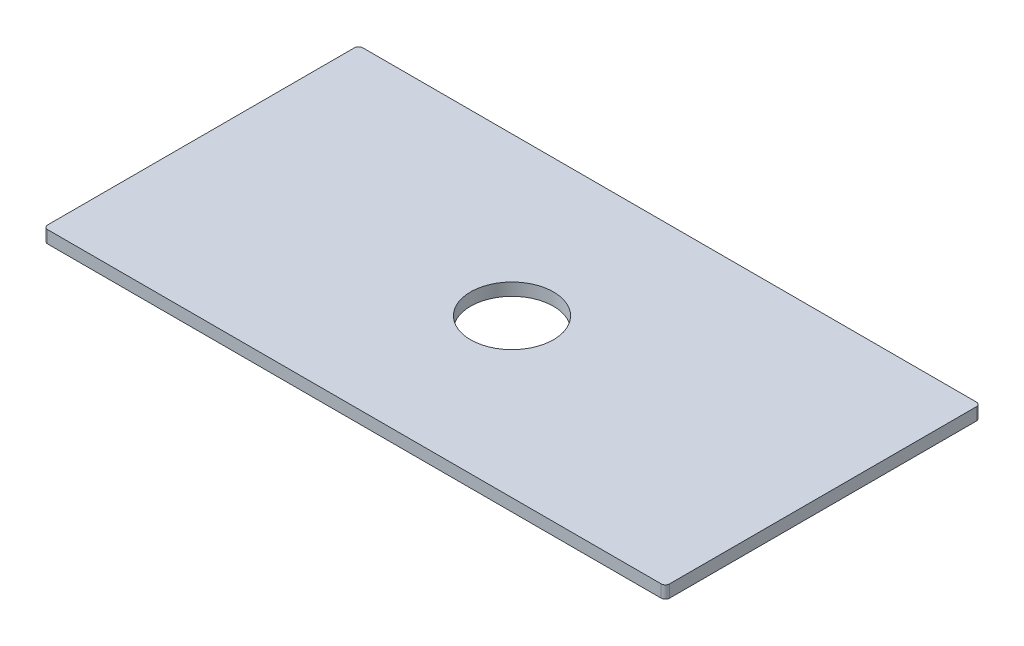
SolidWorks part; units mm, degrees
ref_plane "Front Plane" through (0, 0, 0) normal (0, 0, 1) x (1, 0, 0)
ref_plane "Top Plane" through (0, 0, 0) normal (0, 1, 0) x (1, 0, 0)
ref_plane "Right Plane" through (0, 0, 0) normal (1, 0, 0) x (0, 0, -1)
sketch "Sketch1" plane through (0, 0, 0) normal (0, 1, 0) x (1, 0, 0)
  line L1 (-75, 38) -> (75, 38)
  line L2 (-75, 38) -> (-75, -38)
  line L3 (-75, -38) -> (75, -38)
  line L4 (75, 38) -> (75, -38)
  line L5 (-75, 38) -> (75, -38) construction
  line L6 (-75, -38) -> (75, 38) construction
  point P0 (0, 0)
  dimension "D1" = 150
  dimension "D2" = 76
extrude "Boss-Extrude1" add sketch "Sketch1" along normal blind 3
fillet "Fillet1" radius 1 4 edges at (-75, 1.5, -38) (75, 1.5, -38) (75, 1.5, 38) (-75, 1.5, 38)
sketch "Sketch2" plane through (0, 3, 0) normal (0, 1, 0) x (1, 0, 0)
  circle A0 centre (0, 0) radius 10
  dimension "D1" = 20
extrude "Cut-Extrude1" cut sketch "Sketch2" against normal through all
